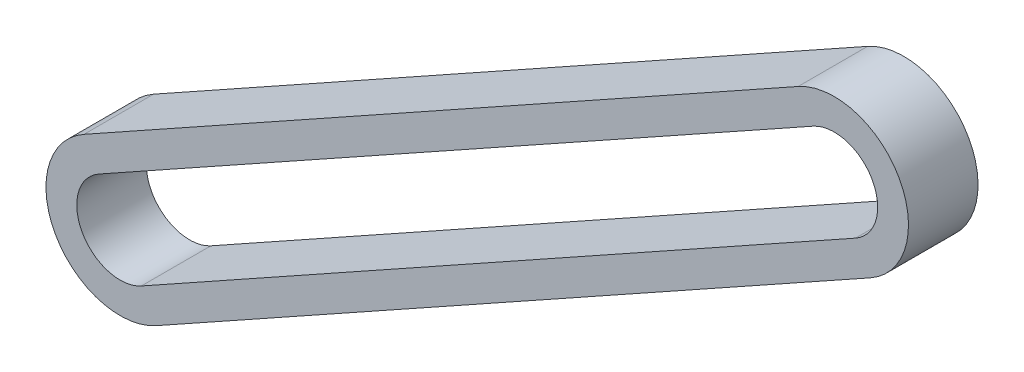
SolidWorks part; units mm, degrees
material "Rubber"
ref_plane "Front Plane" through (0, 0, 0) normal (0, 0, 1) x (1, 0, 0)
ref_plane "Top Plane" through (0, 0, 0) normal (0, 1, 0) x (1, 0, 0)
ref_plane "Right Plane" through (0, 0, 0) normal (1, 0, 0) x (0, 0, -1)
sketch "Sketch1" plane through (0, 0, 0) normal (0, 0, 1) x (1, 0, 0)
  line L0 (0, 0) -> (30.8, 17.1867) construction
  line L1 (-0.9122, 1.6347) -> (29.8878, 18.8214)
  line L2 (0.9122, -1.6347) -> (31.7122, 15.552)
  line L3 (0, 0) -> (30.8, 17.1867) construction
  line L4 (-1.5593, 2.7944) -> (29.2407, 19.9811)
  line L5 (1.5593, -2.7944) -> (32.3593, 14.3923)
  arc A0 (-0.9122, 1.6347) -> (0.9122, -1.6347) centre (0, 0) ccw
  arc A1 (31.7122, 15.552) -> (29.8878, 18.8214) centre (30.8, 17.1867) ccw
  arc A2 (-1.5593, 2.7944) -> (1.5593, -2.7944) centre (0, 0) ccw
  arc A3 (32.3593, 14.3923) -> (29.2407, 19.9811) centre (30.8, 17.1867) ccw
  circle A4 centre (0, 0) radius 1.872 construction
  circle A5 centre (0, 0) radius 3.2 construction
  point P4 (15.4, 8.5934)
  point P9 (15.4, 8.5934)
extrude "Boss-Extrude1" add sketch "Sketch1" against normal blind 3 contours L4 A3 L5 A2
